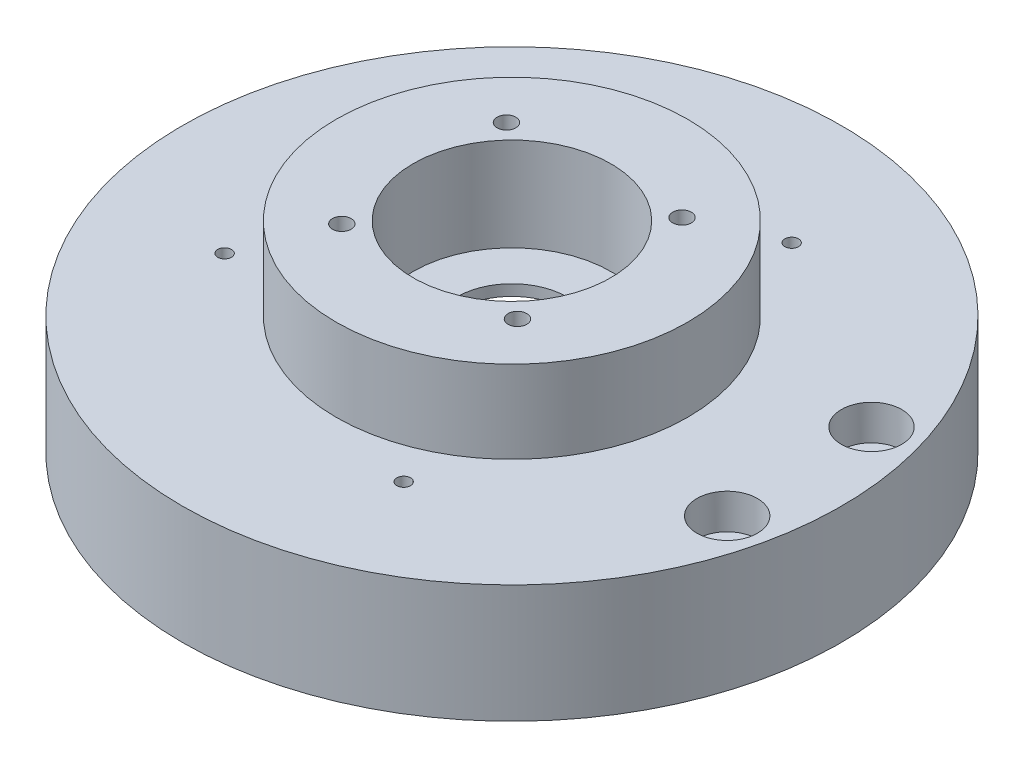
SolidWorks part; units mm, degrees
material "6061 Alloy"
ref_plane "Front Plane" through (0, 0, 0) normal (0, 0, 1) x (1, 0, 0)
ref_plane "Top Plane" through (0, 0, 0) normal (0, 1, 0) x (1, 0, 0)
ref_plane "Right Plane" through (0, 0, 0) normal (1, 0, 0) x (0, 0, -1)
sketch "Sketch1" plane through (0, 0, 0) normal (0, 1, 0) x (1, 0, 0)
  circle A0 centre (0, 0) radius 60
  dimension "D1" = 120
extrude "Boss-Extrude1" add sketch "Sketch1" along normal blind 36.5
sketch "Sketch2" plane through (0, 0, 0) normal (0, -1, 0) x (-1, 0, 0)
  circle A2 centre (0, 0) radius 55
  circle A3 centre (0, 0) radius 50
  circle A4 centre (0, 0) radius 60 construction
  dimension "D1" = 5
  dimension "D2" = 5
extrude "Cut-Extrude1" cut sketch "Sketch2" against normal blind 5 contours A2 A3
sketch "Sketch4" plane through (0, 0, 0) normal (0, 0, 1) x (1, 0, 0)
  line L0 (42, 0) -> (42, 9)
  line L1 (-50, 0) -> (50, 0) construction
  line L2 (42, 9) -> (32.5, 9)
  line L3 (32.5, 9) -> (32.5, 16.5)
  line L5 (0, 30.3215) -> (0, 0)
  line L6 (0, 0) -> (42, 0)
  line L7 (0, 0) -> (0, 32.1539) construction
  line L8 (32.5, 16.5) -> (29, 16.5)
  line L9 (29, 16.5) -> (29, 17.5)
  line L10 (29, 17.5) -> (10, 17.5)
  line L11 (10, 17.5) -> (10, 30.3215)
  line L12 (10, 30.3215) -> (0, 30.3215)
  line L13 (-60, 0) -> (60, 0) construction
  dimension "D1" = 84
  dimension "D2" = 9
  dimension "D3" = 16.5
  dimension "D4" = 29
  dimension "D5" = 20
  dimension "D6" = 65
  dimension "D7" = 17.5
revolve "Cut-Revolve1" cut sketch "Sketch4" angle 360 about L7
sketch "Sketch5" plane through (0, 0, 0) normal (0, 0, 1) x (1, 0, 0)
  line L0 (60, 36.5) -> (-60, 36.5) construction
  line L1 (0, 36.5) -> (18, 36.5)
  line L2 (0, 36.5) -> (0, 19.5)
  line L3 (0, 19.5) -> (18, 19.5)
  line L4 (18, 36.5) -> (18, 19.5)
  line L5 (0, 19.5) -> (0, 62.8395) construction
  dimension "D1" = 36
  dimension "D2" = 17
revolve "Cut-Revolve2" cut sketch "Sketch5" angle 360 about L2
hole_wizard "CBORE for M6 Hex Socket Head Cap Screw1" positions "Sketch6" profile "Sketch7" counterbore size "M6" standard "ISO" end condition through all
sketch "Sketch6" plane through (0, 36.5, 0) normal (0, 1, 0) x (1, 0, 0)
  arc A0 (53.9866, -10.5096) -> (49.0959, -9.4651) centre (51.1242, -11.9402) ccw construction
  arc A1 (48.381, 12.6204) -> (53.1939, 13.979) centre (50.2449, 15.2216) ccw construction
  point P0 (51.1242, -11.9402)
  point P2 (50.2449, 15.2216)
sketch "Sketch7" plane through (51.1242, 36.5, 11.9402) normal (1, 0, 0) x (0, 0, 1)
  line L0 (0, 0) -> (0, 36.5)
  line L1 (0, 36.5) -> (3.2, 36.5)
  line L3 (3.2, 36.5) -> (3.2, 21.4)
  line L4 (3.2, 21.4) -> (5.5, 21.4)
  line L5 (5.5, 21.4) -> (5.5, 0)
  line L7 (5.5, 0) -> (0, 0)
  line L11 (0, -6.35) -> (0, 107.95) construction
  dimension "Thru Hole Dia." = 6.4
  dimension "Thru Hole Depth" = 36.5
  dimension "C'Bore Dia." = 11
  dimension "C'Bore Depth" = 21.4
hole_wizard "M3 Clearance Hole1" positions "Sketch8" profile "Sketch9" hole size "M3" standard "ISO" end condition through all
sketch "Sketch8" plane through (0, 36.5, 0) normal (0, 1, 0) x (1, 0, 0)
  point P0 (14.9846, 15.9872)
  point P3 (15.9872, -14.9846)
  point P6 (-14.9846, -15.9872)
  point P9 (-15.9872, 14.9846)
sketch "Sketch9" plane through (14.9846, 36.5, -15.9872) normal (1, 0, 0) x (0, 0, 1)
  line L0 (0, 0) -> (0, 36.5)
  line L1 (0, 36.5) -> (1.7, 36.5)
  line L2 (1.7, 36.5) -> (1.7, 0)
  line L5 (1.7, 0) -> (0, 0)
  line L11 (0, -6.35) -> (0, 107.95) construction
  dimension "Thru Hole Dia." = 3.4
  dimension "Thru Hole Depth" = 36.5
hole_wizard "CBORE for M3 Hex Socket Head Cap Screw1" positions "Sketch10" profile "Sketch11" counterbore size "M3" standard "ISO" end condition through all
sketch "Sketch10" plane through (0, 17.5, 0) normal (0, -1, 0) x (-1, 0, 0)
  point P0 (15.9872, 14.9846)
  point P3 (-14.9846, 15.9872)
  point P6 (-15.9872, -14.9846)
  point P9 (14.9846, -15.9872)
sketch "Sketch11" plane through (-15.9872, 17.5, -14.9846) normal (1, 0, 0) x (0, 0, -1)
  line L0 (0, 0) -> (0, 19)
  line L1 (0, 19) -> (1.7, 19)
  line L3 (1.7, 19) -> (1.7, 5.4)
  line L4 (1.7, 5.4) -> (3.25, 5.4)
  line L5 (3.25, 5.4) -> (3.25, 0)
  line L7 (3.25, 0) -> (0, 0)
  line L11 (0, -6.35) -> (0, 107.95) construction
  dimension "Thru Hole Dia." = 3.4
  dimension "Thru Hole Depth" = 19
  dimension "C'Bore Dia." = 6.5
  dimension "C'Bore Depth" = 5.4
sketch "Sketch12" plane through (0, 0, 0) normal (0, 0, 1) x (1, 0, 0)
  line L1 (-60, 36.5) -> (-32, 36.5)
  line L2 (-60, 36.5) -> (-60, 21.5)
  line L3 (-60, 21.5) -> (-32, 21.5)
  line L4 (-32, 36.5) -> (-32, 21.5)
  dimension "D1" = 28
  dimension "D2" = 15
revolve "Cut-Revolve3" cut sketch "Sketch12" angle 360 about axis through (0, 36.5, 0) along (0, -1, 0)
hole_wizard "M3 Tapped Hole1" positions "Sketch13" profile "Sketch14" tap size "M3" standard "ISO"
sketch "Sketch13" plane through (0, 21.5, 0) normal (0, 1, 0) x (1, 0, 0)
  point P0 (13.9362, 36.9866)
  point P3 (-36.9866, 13.9362)
  point P6 (-36.0079, -16.2991)
  point P9 (16.2991, -36.0079)
sketch "Sketch14" plane through (13.9362, 21.5, -36.9866) normal (1, 0, 0) x (0, 0, 1)
  line L0 (0, 0) -> (0, 8.2511)
  line L1 (0, 8.2511) -> (1.25, 7.5)
  line L2 (1.25, 7.5) -> (1.25, 0)
  line L5 (1.25, 0) -> (0, 0)
  line L10 (0, 8.2511) -> (-1.25, 7.5) construction
  line L11 (0, -6.35) -> (0, 107.95) construction
  dimension "Tap Drill Dia." = 2.5
  dimension "Tap Drill Depth" = 7.5
  dimension "Drill Angle" = 118
